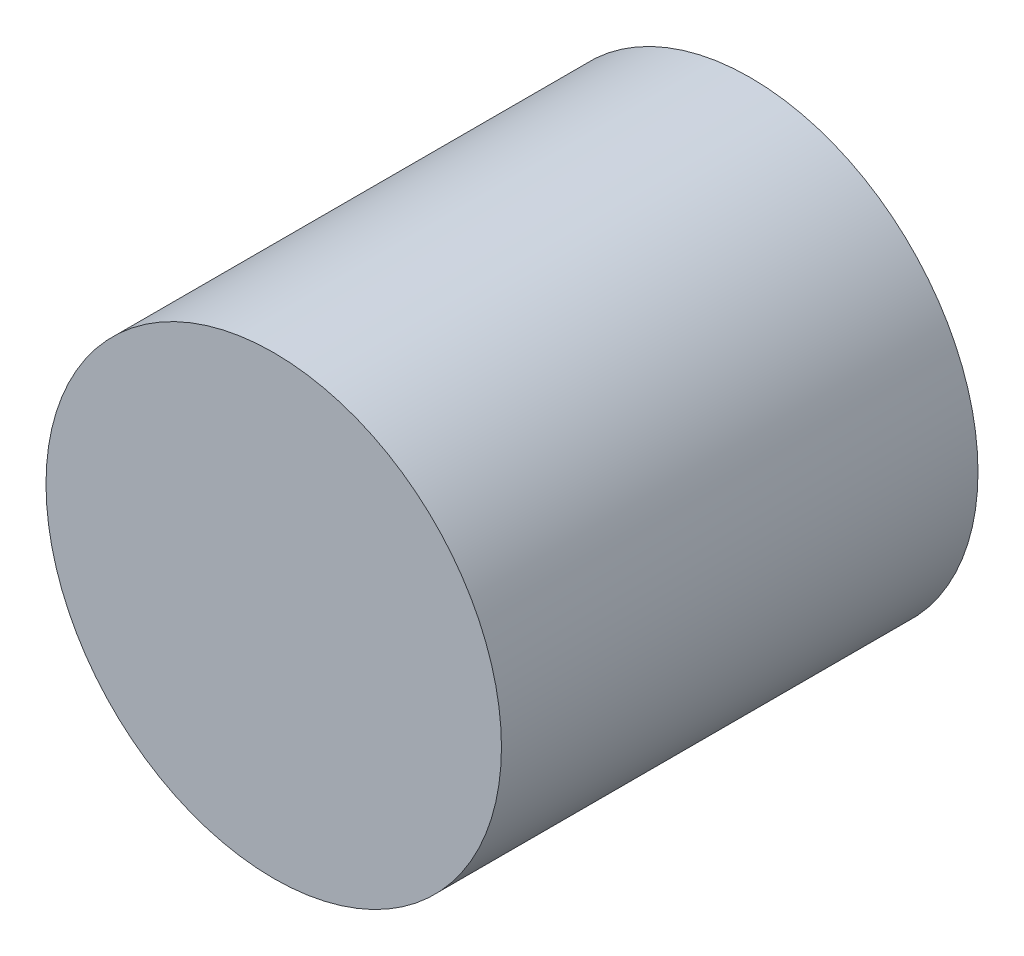
SolidWorks part; units mm, degrees
ref_plane "Front Plane" through (0, 0, 0) normal (0, 0, 1) x (1, 0, 0)
ref_plane "Top Plane" through (0, 0, 0) normal (0, 1, 0) x (1, 0, 0)
ref_plane "Right Plane" through (0, 0, 0) normal (1, 0, 0) x (0, 0, -1)
sketch "Sketch1" plane through (0, 0, 0) normal (0, 0, 1) x (1, 0, 0)
  circle A0 centre (0, 0) radius 49.5234
extrude "Boss-Extrude1" add sketch "Sketch1" against normal blind 103.632
